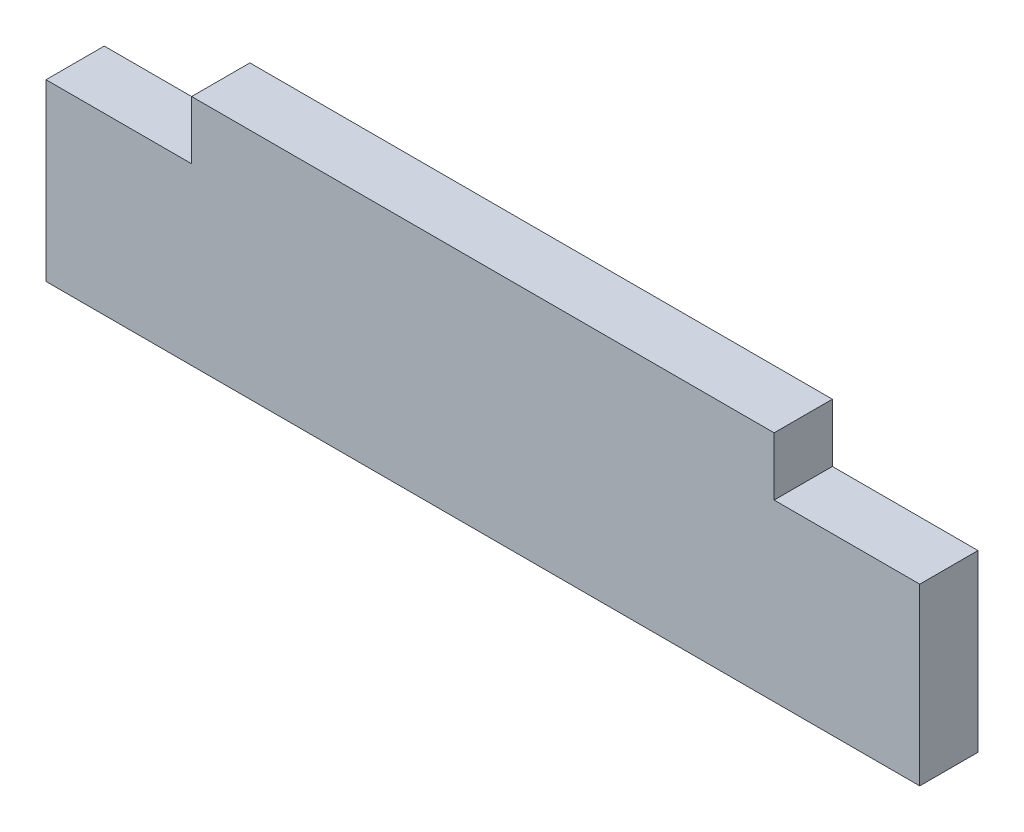
SolidWorks part; units mm, degrees
material "Acrylic (Medium-high impact)"
ref_plane "Front Plane" through (0, 0, 0) normal (0, 0, 1) x (1, 0, 0)
ref_plane "Top Plane" through (0, 0, 0) normal (0, 1, 0) x (1, 0, 0)
ref_plane "Right Plane" through (0, 0, 0) normal (1, 0, 0) x (0, 0, -1)
sketch "Sketch1" plane through (0, 0, 0) normal (0, 0, 1) x (1, 0, 0)
  line L0 (-22.5, 0) -> (-22.5, 9)
  line L1 (-22.5, 9) -> (-15, 9)
  line L2 (-15, 9) -> (-15, 12)
  line L3 (-15, 12) -> (15, 12)
  line L4 (15, 12) -> (15, 9)
  line L5 (15, 9) -> (22.5, 9)
  line L6 (22.5, 9) -> (22.5, 0)
  line L7 (22.5, 0) -> (-22.5, 0)
  point P6 (0, 0)
  point P9 (0, 12)
  dimension "D1" = 30
  dimension "D2" = 45
  dimension "D3" = 3
  dimension "D4" = 9
extrude "Boss-Extrude1" add sketch "Sketch1" along normal mid plane 3
